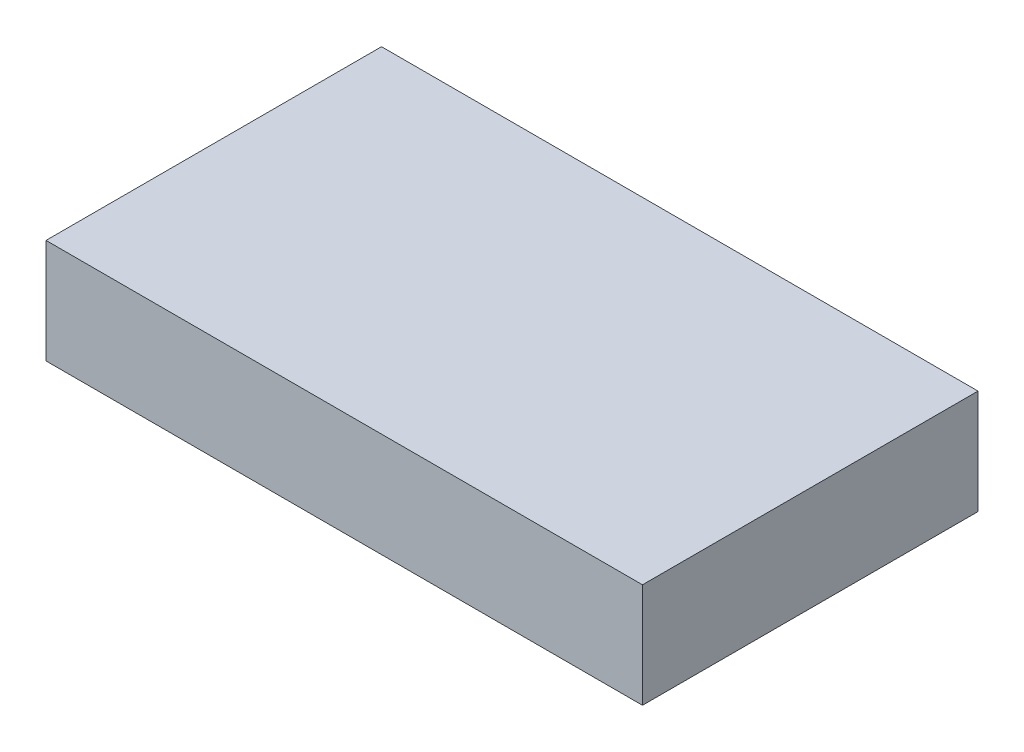
SolidWorks part; units mm, degrees
ref_plane "Front Plane" through (0, 0, 0) normal (0, 0, 1) x (1, 0, 0)
ref_plane "Top Plane" through (0, 0, 0) normal (0, 1, 0) x (1, 0, 0)
ref_plane "Right Plane" through (0, 0, 0) normal (1, 0, 0) x (0, 0, -1)
sketch "Sketch1" plane through (0, 0, 0) normal (0, 0, 1) x (1, 0, 0)
  line L1 (0, 0) -> (8, 0)
  line L2 (0, 0) -> (0, 1.4)
  line L3 (0, 1.4) -> (8, 1.4)
  line L4 (8, 0) -> (8, 1.4)
  dimension "D1" = 8
  dimension "D2" = 1.4
extrude "Boss-Extrude1" add sketch "Sketch1" along normal blind 4.5
sketch "Sketch2" plane through (0, 0, 0) normal (0, -1, 0) x (1, 0, 0)
  line L0 (8, 4.5) -> (8, 0) construction
  line L1 (9.5, 0) -> (8, 0)
  line L2 (9.5, 0) -> (9.5, 6)
  line L3 (9.5, 6) -> (-1.5, 6)
  line L4 (-1.5, 0) -> (-1.5, 6)
  line L5 (4, 6) -> (4, 0) construction
  line L6 (9.5, 3) -> (-1.5, 3) construction
  line L7 (0, 4.5) -> (0, 0) construction
  line L9 (0, 4.5) -> (8, 4.5) construction
  line L10 (0, 0) -> (0, 4.5)
  line L11 (0, 4.5) -> (8, 4.5)
  line L12 (8, 4.5) -> (8, 0)
  line L13 (0, 0) -> (-1.5, 0)
  line L14 (-1.5, 0) -> (0, 0)
  point P0 (4, 3)
  dimension "D1" = 1.5
  dimension "D2" = 1.5
  dimension "D4" = 1.5
